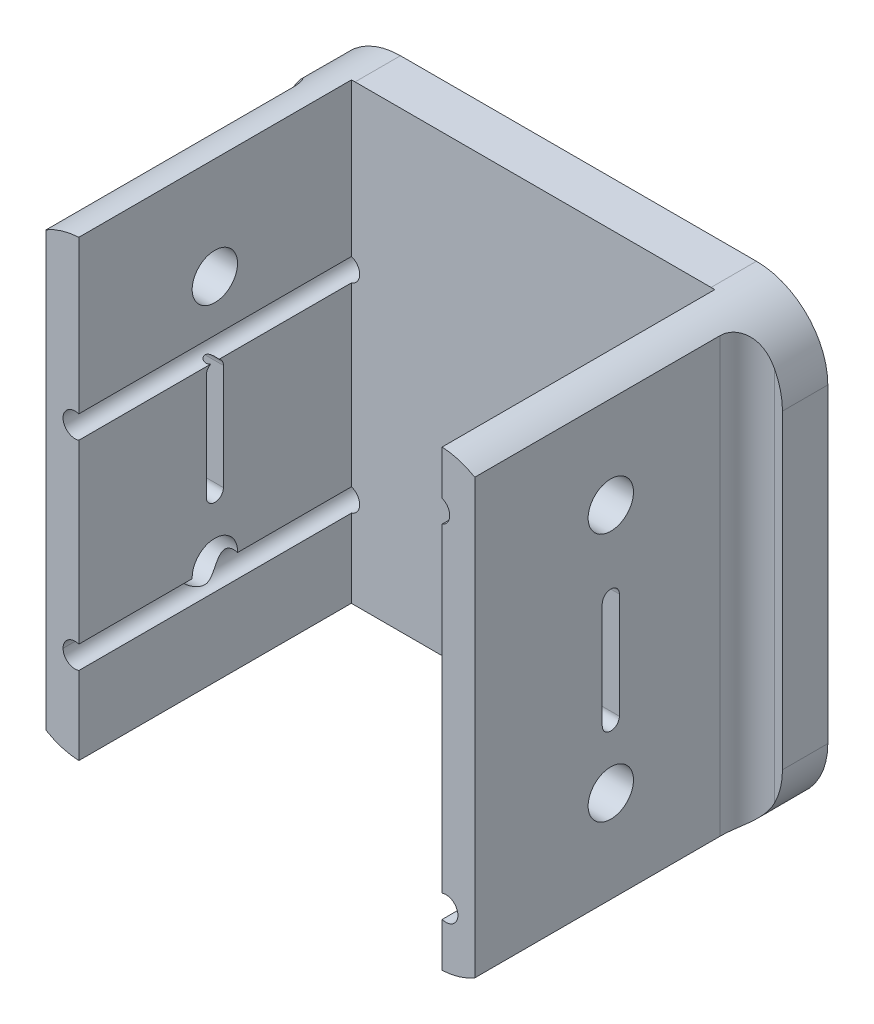
SolidWorks part; units mm, degrees
material "ABS"
ref_plane "Front Plane" through (0, 0, 0) normal (0, 0, 1) x (1, 0, 0)
ref_plane "Top Plane" through (0, 0, 0) normal (0, 1, 0) x (1, 0, 0)
ref_plane "Right Plane" through (0, 0, 0) normal (1, 0, 0) x (0, 0, -1)
sketch "Sketch3" plane through (0, 0, 0) normal (0, 1, 0) x (1, 0, 0)
  line L1 (0, 0) -> (50.8762, 0)
  line L2 (0, 0) -> (0, -38.1762)
  line L3 (-4.572, -38.1762) -> (0, -38.1762)
  line L4 (50.8762, 0) -> (50.8762, -38.1762)
  line L5 (55.4482, -3.81) -> (55.4482, -38.1762)
  line L7 (-4.572, -3.81) -> (-4.572, -38.1762)
  line L8 (0, -38.1762) -> (50.8762, -38.1762) construction
  line L9 (50.8762, -38.1762) -> (55.4482, -38.1762)
  line L10 (-4.572, 4.572) -> (-4.572, -42.7482) construction
  line L11 (-4.572, -42.7482) -> (55.4482, -42.7482) construction
  line L12 (55.4482, 4.572) -> (55.4482, -42.7482) construction
  line L13 (0, 0) -> (50.8762, 0) construction
  line L14 (-9.4869, 6.35) -> (60.3631, 6.35)
  line L15 (-9.4869, 6.35) -> (-9.4869, 0)
  line L16 (-9.4869, 0) -> (-8.382, 0)
  line L17 (60.3631, 6.35) -> (60.3631, 0)
  line L18 (-4.572, 4.572) -> (55.4482, 4.572) construction
  line L19 (0, 0) -> (50.8762, 0)
  line L20 (59.2582, 0) -> (60.3631, 0)
  arc A0 (59.2582, 0) -> (55.4482, -3.81) centre (59.2582, -3.81) ccw
  arc A1 (-8.382, 0) -> (-4.572, -3.81) centre (-8.382, -3.81) cw
  point P15 (25.4381, 6.35)
  point P16 (25.4381, 6.35)
  point P22 (25.4381, 0)
  dimension "D6" = 3.81
  dimension "D1" = 50.8762
  dimension "D2" = 38.1762
  dimension "D4" = 69.85
  dimension "D5" = 6.35
  dimension "D3" = 4.572
extrude "Boss-Extrude2" add sketch "Sketch3" along normal blind 63.5 contours L16 A1 L7 L3 L2 L1 L4 L9 L5 A0 L20 L17 L14 L15
sketch "Sketch4" plane through (55.4482, 0, 0) normal (1, 0, 0) x (0, 0, -1)
  line L0 (-19.1262, 49.2125) -> (-19.1262, 14.2875) construction
  line L1 (-38.1762, 63.5) -> (-38.1762, 0) construction
  circle A0 centre (-19.1262, 49.2125) radius 3.175
  circle A1 centre (-19.1262, 14.2875) radius 3.175
  point P4 (-38.1762, 31.75)
  point P5 (-19.1262, 31.75)
  dimension "D1" = 6.35
  dimension "D2" = 34.925
  dimension "D3" = 19.05
extrude "Cut-Extrude1" cut sketch "Sketch4" against normal through all
sketch "Sketch5" plane through (0, 0, -6.35) normal (0, 0, -1) x (-1, 0, 0)
  line L0 (0.5271, 40.4686) -> (0.5271, 12.5413) construction
  line L1 (-50.2602, 55.7085) -> (-51.4032, 55.7085) construction
  line L2 (-51.4032, 55.7085) -> (-51.4032, 7.7915) construction
  line L3 (-51.4032, 31.75) -> (0.527, 31.75) construction
  line L4 (9.4869, 63.5) -> (9.4869, 0) construction
  line L5 (9.4869, 0) -> (-60.3631, 0) construction
  circle A0 centre (0.5271, 12.5413) radius 1.6828
  circle A1 centre (-51.4032, 7.7915) radius 1.6827
  circle A2 centre (-50.2602, 55.7085) radius 1.6827
  circle A3 centre (0.5271, 40.4686) radius 1.6827
  point P8 (-51.4032, 31.75)
  point P11 (-51.4032, 31.75)
  point P13 (-25.4381, 31.75)
  point P14 (9.4869, 31.75)
  point P15 (-25.4381, 0)
  dimension "D1" = 3.3655
  dimension "D2" = 27.9273
  dimension "D3" = 47.9171
  dimension "D4" = 1.143
  dimension "D5" = 51.9303
  dimension "D6" = 4.7498
extrude "Cut-Extrude2" cut sketch "Sketch5" against normal up to next
fillet "Fillet1" radius 10 4 edges at (60.3631, 63.5, -3.175) (60.3631, 0, -3.175) (-9.4869, 0, -3.175) (-9.4869, 63.5, -3.175)
sketch "Sketch6" plane through (-4.572, 0, 0) normal (-1, 0, 0) x (0, 0, 1)
  line L0 (19.1262, 23.0033) -> (19.1262, 37.8222) construction
  line L1 (17.9273, 23.0033) -> (17.9273, 37.8222)
  line L2 (20.3251, 23.0033) -> (20.3251, 37.8222)
  line L3 (3.81, 1.3894) -> (38.1762, 1.3894) construction
  line L4 (19.1262, 49.2125) -> (19.1262, 46.0375) construction
  arc A0 (17.9273, 23.0033) -> (20.3251, 23.0033) centre (19.1262, 23.0033) ccw
  arc A1 (20.3251, 37.8222) -> (17.9273, 37.8222) centre (19.1262, 37.8222) ccw
  circle A2 centre (19.1262, 49.2125) radius 3.175 construction
  point P2 (19.1262, 30.4127)
  point P15 (19.1262, 47.625)
  dimension "D3" = 1.1989
  dimension "D1" = 14.819
  dimension "D2" = 29.0233
extrude "Cut-Extrude3" cut sketch "Sketch6" against normal through all contours L1 A1 L2 A0
